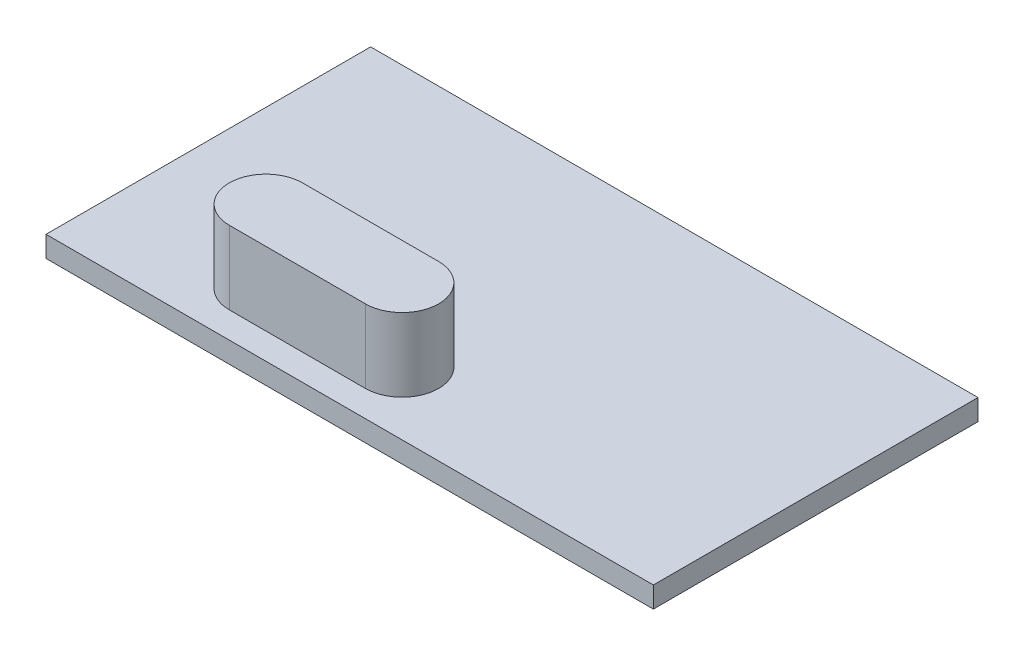
SolidWorks part; units mm, degrees
ref_plane "Front Plane" through (0, 0, 0) normal (0, 0, 1) x (1, 0, 0)
ref_plane "Top Plane" through (0, 0, 0) normal (0, 1, 0) x (1, 0, 0)
ref_plane "Right Plane" through (0, 0, 0) normal (1, 0, 0) x (0, 0, -1)
sketch "Sketch1" plane through (0, 0, 0) normal (0, 1, 0) x (1, 0, 0)
  line L1 (-14.5, -7.75) -> (14.5, -7.75)
  line L2 (-14.5, -7.75) -> (-14.5, 7.75)
  line L3 (-14.5, 7.75) -> (14.5, 7.75)
  line L4 (14.5, -7.75) -> (14.5, 7.75)
  line L5 (-14.5, -7.75) -> (14.5, 7.75) construction
  line L6 (-14.5, 7.75) -> (14.5, -7.75) construction
  point P0 (0, 0)
  dimension "D1" = 29
  dimension "D2" = 15.5
extrude "Boss-Extrude1" add sketch "Sketch1" along normal blind 1
sketch "Sketch2" plane through (0, 1, 0) normal (0, 1, 0) x (1, 0, 0)
  line L0 (-7, -4.75) -> (-0.5, -4.75) construction
  line L1 (-7, -3) -> (-0.5, -3)
  line L2 (-7, -6.5) -> (-0.5, -6.5)
  line L3 (-14.5, 7.75) -> (-14.5, -7.75) construction
  line L4 (-14.5, -7.75) -> (14.5, -7.75) construction
  arc A0 (-7, -3) -> (-7, -6.5) centre (-7, -4.75) ccw
  arc A1 (-0.5, -6.5) -> (-0.5, -3) centre (-0.5, -4.75) ccw
  point P2 (-3.75, -4.75)
  dimension "D1" = 3.5
  dimension "D2" = 6.5
  dimension "D3" = 7.5
  dimension "D4" = 3
extrude "Boss-Extrude2" add sketch "Sketch2" along normal blind 3.5
sketch "Sketch4" plane through (0, 0, 0) normal (0, -1, 0) x (1, 0, 0)
  line L0 (14.5, -7.75) -> (-14.5, -7.75) construction
  line L1 (-14.3, 2.75) -> (-9.3, 2.75)
  line L2 (-14.3, 2.75) -> (-14.3, -7.25)
  line L3 (-14.3, -7.25) -> (-9.3, -7.25)
  line L4 (-9.3, 2.75) -> (-9.3, -7.25)
  line L5 (-14.5, -7.75) -> (-14.5, 7.75) construction
  dimension "D1" = 5
  dimension "D2" = 10
  dimension "D3" = 0.5
  dimension "D4" = 0.2
extrude "Boss-Extrude3" add sketch "Sketch4" along normal blind 3
